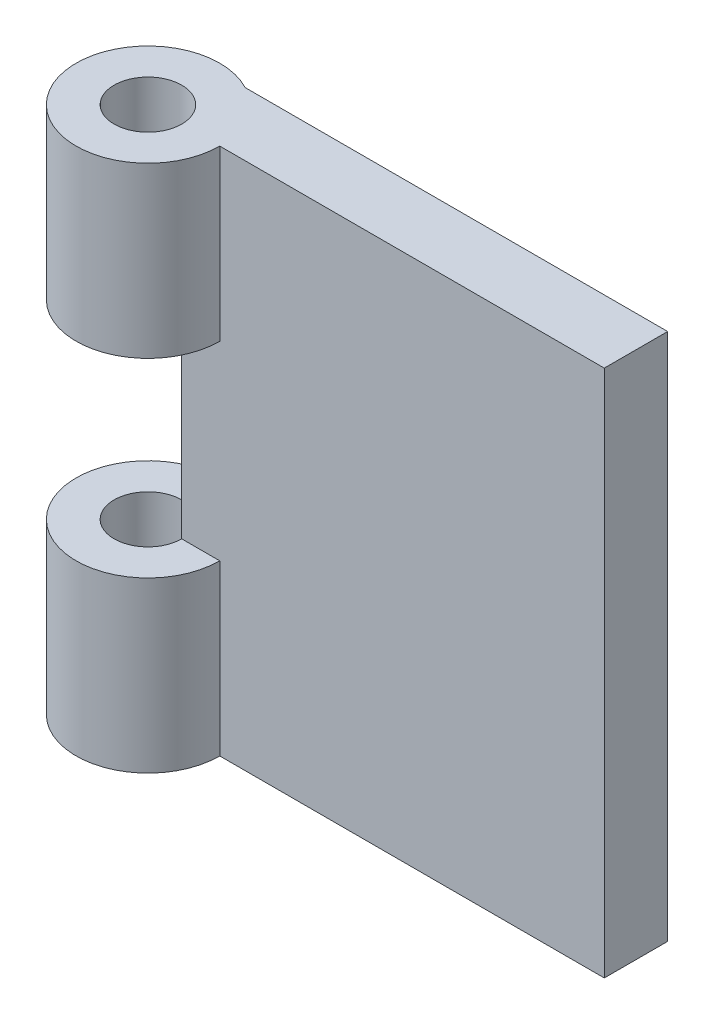
SolidWorks part; units mm, degrees
ref_plane "Front Plane" through (0, 0, 0) normal (1, 0, 0) x (0, 1, 0)
ref_plane "Top Plane" through (0, 0, 0) normal (0, 0, 1) x (0, 1, 0)
ref_plane "Right Plane" through (0, 0, 0) normal (0, 1, 0) x (-1, 0, 0)
sketch "Sketch2" plane through (0, 0, 0) normal (0, 0, 1) x (0, 1, 0)
  line L1 (-12.5, 10) -> (12.5, 10)
  line L2 (-12.5, 10) -> (-12.5, -10)
  line L3 (-12.5, -10) -> (12.5, -10)
  line L4 (12.5, 10) -> (12.5, -10)
  line L5 (-12.5, 10) -> (12.5, -10) construction
  line L6 (-12.5, -10) -> (12.5, 10) construction
  point P0 (0, 0)
  dimension "D1" = 25
  dimension "D2" = 20
extrude "Boss-Extrude1" add sketch "Sketch2" along normal blind 3
sketch "Sketch3" plane through (22.5, 12.5, 0) normal (0, 1, 0) x (-1, 0, 0)
  line L0 (32.5, 3) -> (32.5, 0) construction
  circle A0 centre (34.1, 3) radius 3.4
  circle A1 centre (34.1, 3) radius 1.6
  dimension "D2" = 3.2
extrude "Boss-Extrude2" add sketch "Sketch3" against normal blind 8
pattern_linear "LPattern1" count 2 spacing 17 along (0, -1, 0) of "Boss-Extrude2"
